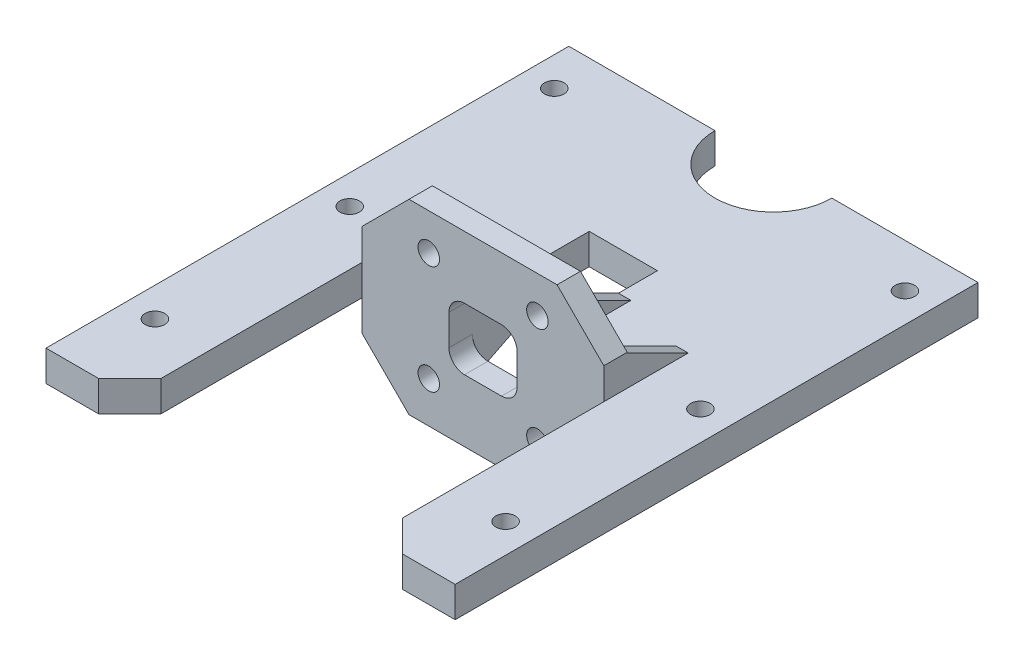
SolidWorks part; units mm, degrees
ref_plane "Front Plane" through (0, 0, 0) normal (0, 0, 1) x (1, 0, 0)
ref_plane "Top Plane" through (0, 0, 0) normal (0, 1, 0) x (1, 0, 0)
ref_plane "Right Plane" through (0, 0, 0) normal (1, 0, 0) x (0, 0, -1)
sketch "Sketch1" plane through (0, 0, 0) normal (0, 1, 0) x (1, 0, 0)
  line L0 (0, 0) -> (0, 28440.1022) construction
  line L1 (28.575, 44.7251) -> (-28.575, 44.7251) construction
  line L2 (-28.575, 78.0626) -> (28.575, 78.0626) construction
  line L3 (-28.575, 78.0626) -> (-28.575, 12.9751) construction
  line L4 (-28.575, 12.9751) -> (28.575, 12.9751) construction
  line L5 (28.575, 78.0626) -> (28.575, 12.9751) construction
  line L6 (-19.685, 0) -> (-19.685, 41.689)
  line L7 (-33.3375, 0) -> (33.3375, 0)
  line L8 (-33.3375, 0) -> (-33.3375, 85.1989)
  line L9 (-33.3375, 85.1989) -> (33.3375, 85.1989)
  line L10 (33.3375, 0) -> (33.3375, 85.1989)
  line L11 (-19.685, 41.689) -> (19.685, 41.689)
  line L12 (19.685, 41.689) -> (19.685, 0)
  line L13 (-5.5563, 41.689) -> (-5.5562, 60.739)
  line L14 (-5.5562, 60.739) -> (5.5562, 60.739)
  line L15 (5.5562, 60.739) -> (5.5563, 41.689)
  circle A0 centre (-28.575, 78.0626) radius 1.5875
  circle A1 centre (28.575, 78.0626) radius 1.5875
  circle A2 centre (28.575, 44.7251) radius 1.5875
  circle A3 centre (28.575, 12.9751) radius 1.5875
  circle A4 centre (-28.575, 12.9751) radius 1.5875
  circle A5 centre (-28.575, 44.7251) radius 1.5875
  arc A6 (-9.525, 85.1989) -> (9.525, 85.1989) centre (0, 85.1989) ccw
  point P13 (0, 12.9751)
  point P24 (0, 41.689)
  point P29 (0, 60.739)
  dimension "D2" = 3.175
  dimension "D9" = 19.05
  dimension "D1" = 57.15
  dimension "D3" = 31.75
  dimension "D4" = 33.3375
  dimension "D5" = 66.675
  dimension "D6" = 39.37
  dimension "D7" = 19.05
  dimension "D8" = 11.1125
extrude "Boss-Extrude1" add sketch "Sketch1" along normal blind 5 contours A6 L9 L8 L7 L6 L11 L13 L14 L15 L12 L10 A5 A4 A3 A2 A1 A0
sketch "Sketch2" plane through (0, 0, -41.689) normal (0, 0, 1) x (1, 0, 0)
  line L0 (-19.685, 5) -> (-5.5563, 5) construction
  line L1 (-19.685, 17.7) -> (19.685, 17.7)
  line L2 (-19.685, 17.7) -> (-19.685, -12.7)
  line L3 (-19.685, -12.7) -> (19.685, -12.7)
  line L4 (19.685, 17.7) -> (19.685, -12.7)
  line L5 (-19.685, 0) -> (-5.5563, 0) construction
  line L6 (-19.685, 5) -> (-19.685, 0) construction
  line L7 (19.685, 5) -> (19.685, 0) construction
  dimension "D1" = 12.7
  dimension "D2" = 12.7
  dimension "D3" = 0
  dimension "D4" = 0
extrude "Boss-Extrude2" add sketch "Sketch2" along normal blind 3.81
sketch "Sketch3" plane through (0, 0, -41.689) normal (0, 0, -1) x (-1, 0, 0)
  line L0 (-5.5563, 5) -> (-19.685, 5) construction
  line L1 (-5.5562, 7.54) -> (5.5563, 7.54)
  line L2 (-5.5562, 7.54) -> (-5.5562, -2.54)
  line L3 (-5.5562, -2.54) -> (5.5563, -2.54)
  line L4 (5.5563, 7.54) -> (5.5563, -2.54)
  line L5 (19.685, 0) -> (5.5563, 0) construction
  dimension "D1" = 2.54
  dimension "D2" = 2.54
extrude "Cut-Extrude1" cut sketch "Sketch3" against normal blind 3.81
fillet "Fillet1" radius 2.54 4 edges at (5.5562, -2.54, -39.784) (-5.5563, -2.54, -39.784) (5.5562, 7.54, -39.784) (-5.5563, 7.54, -39.784)
chamfer "Chamfer1" distance 7.62 angle 45 4 edges at (-19.685, -12.7, -39.784) (19.685, -12.7, -39.784) (19.685, 17.7, -39.784) (-19.685, 17.7, -39.784)
chamfer "Chamfer2" distance 5.08 angle 45 2 edges at (-19.685, 2.5, 0) (19.685, 2.5, 0)
sketch "Sketch4" plane through (5.5563, 0, 0) normal (-1, 0, 0) x (0, 0, 1)
  line L0 (-41.689, 5) -> (-54.389, 5)
  line L1 (-60.739, 5) -> (-41.689, 5) construction
  line L2 (-54.389, 5) -> (-41.689, 11.35)
  line L3 (-41.689, 11.35) -> (-41.689, 5)
  dimension "D1" = 6.35
  dimension "D2" = 12.7
extrude "Boss-Extrude3" add sketch "Sketch4" against normal blind 2.032
sketch "Sketch5" plane through (-5.5563, 0, 0) normal (1, 0, 0) x (0, 0, -1)
  line L0 (54.389, 5) -> (41.689, 5)
  line L1 (41.689, 5) -> (60.739, 5) construction
  line L2 (41.689, 5) -> (41.689, 11.35)
  line L3 (41.689, 11.35) -> (54.389, 5)
  dimension "D1" = 12.7
  dimension "D2" = 6.35
extrude "Boss-Extrude4" add sketch "Sketch5" against normal blind 2.032
sketch "Sketch6" plane through (-5.5563, 0, 0) normal (1, 0, 0) x (0, 0, -1)
  line L0 (41.689, 0) -> (54.389, 0)
  line L1 (41.689, 0) -> (60.739, 0) construction
  line L2 (54.389, 0) -> (41.689, -6.35)
  line L3 (41.689, -6.35) -> (41.689, 0)
  dimension "D1" = 12.7
  dimension "D2" = 6.35
extrude "Boss-Extrude5" add sketch "Sketch6" against normal blind 2.032
sketch "Sketch7" plane through (5.5563, 0, 0) normal (-1, 0, 0) x (0, 0, 1)
  line L0 (-41.689, 0) -> (-54.389, 0)
  line L1 (-60.739, 0) -> (-41.689, 0) construction
  line L2 (-54.389, 0) -> (-41.689, -6.35)
  line L3 (-41.689, -6.35) -> (-41.689, 0)
  dimension "D1" = 12.7
  dimension "D2" = 6.35
extrude "Boss-Extrude6" add sketch "Sketch7" against normal blind 2.032
sketch "Sketch8" plane through (0, 0, -37.879) normal (0, 0, 1) x (1, 0, 0)
  line L1 (3.0163, -2.54) -> (-3.0163, -2.54) construction
  line L2 (5.5562, 5) -> (5.5562, 0) construction
  circle A0 centre (-8.8417, 11.7164) radius 1.75
  circle A1 centre (8.8582, 11.7211) radius 1.75
  circle A2 centre (8.8582, -5.9789) radius 1.75
  circle A3 centre (-8.8417, -5.9836) radius 1.75
  point P14 (5.5562, 2.5)
  dimension "D1" = 3.5
  dimension "D2" = 3.5
  dimension "D3" = 3.5
  dimension "D4" = 3.5
  dimension "D5" = 17.7
  dimension "D6" = 17.7
  dimension "D7" = 17.7
  dimension "D8" = 17.7
  dimension "D9" = 3.4436
  dimension "D10" = 3.302
  dimension "D11" = 3.302
extrude "Cut-Extrude2" cut sketch "Sketch8" against normal blind 20.32
sketch "Sketch9" plane through (0, 0, -41.689) normal (0, 0, -1) x (-1, 0, 0)
  circle A0 centre (-8.8582, 11.7211) radius 3
  circle A1 centre (8.8417, 11.7164) radius 3
  circle A2 centre (8.8417, -5.9836) radius 3
  circle A3 centre (-8.8582, -5.9789) radius 3
  dimension "D1" = 6
  dimension "D2" = 6
  dimension "D3" = 6
  dimension "D4" = 6
extrude "Cut-Extrude3" cut sketch "Sketch9" along normal blind 10.16
sketch "Sketch10" plane through (19.685, 0, 0) normal (1, 0, 0) x (0, 0, -1)
  line L0 (41.689, 9.9711) -> (51.6312, 5)
  line L1 (54.389, 5) -> (41.689, 5) construction
  line L2 (51.6312, 5) -> (41.689, 5)
  line L3 (41.689, 5) -> (41.689, 9.9711)
  line L4 (41.689, -5.08) -> (51.849, 0)
  line L5 (0, 0) -> (85.1989, 0) construction
  line L6 (51.849, 0) -> (41.689, 0)
  line L7 (41.689, 0) -> (41.689, -5.08)
extrude "Boss-Extrude7" add sketch "Sketch10" against normal blind 2.032
sketch "Sketch11" plane through (-19.685, 0, 0) normal (-1, 0, 0) x (0, 0, 1)
  line L0 (-41.689, 10.08) -> (-51.849, 5)
  line L1 (0, 5) -> (-85.1989, 5) construction
  line L2 (-51.849, 5) -> (-41.689, 5)
  line L3 (-41.689, 5) -> (-41.689, 10.08)
  line L4 (-41.689, -5.08) -> (-41.689, 0)
  line L5 (-41.689, 0) -> (-51.849, 0)
  line L6 (0, 0) -> (-85.1989, 0) construction
  line L7 (-51.849, 0) -> (-41.689, -5.08)
extrude "Boss-Extrude8" add sketch "Sketch11" against normal blind 2.032
